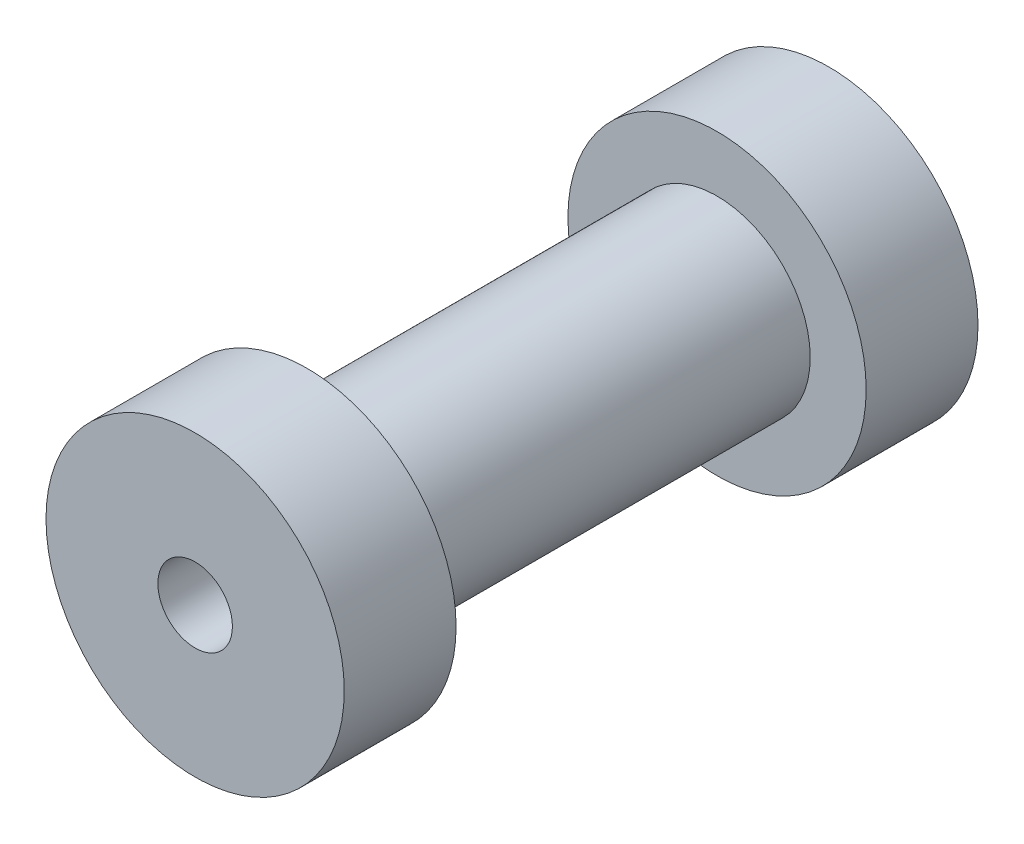
SolidWorks part; units mm, degrees
ref_plane "Alzado" through (0, 0, 0) normal (0, 0, 1) x (1, 0, 0)
ref_plane "Planta" through (0, 0, 0) normal (0, 1, 0) x (1, 0, 0)
ref_plane "Vista lateral" through (0, 0, 0) normal (1, 0, 0) x (0, 0, -1)
sketch "Croquis1" plane through (0, 0, 0) normal (0, 0, 1) x (1, 0, 0)
  circle A0 centre (0, 0) radius 4
  dimension "D1" = 8
extrude "Saliente-Extruir1" add sketch "Croquis1" along normal blind 17
sketch "Croquis2" plane through (0, 0, 17) normal (0, 0, 1) x (1, 0, 0)
  circle A0 centre (0, 0) radius 1
  dimension "D1" = 2
extrude "Cortar-Extruir1" cut sketch "Croquis2" against normal through all
ref_axis "Eje1" through (0, 0, 17) along (0, 0, -1)
sketch "Croquis3" plane through (0, 0, 0) normal (1, 0, 0) x (0, 0, -1)
  line L0 (0, 4) -> (-17, 4) construction
  line L1 (-3, 4) -> (-14, 4)
  line L2 (-3, 4) -> (-3, 2.5)
  line L3 (-3, 2.5) -> (-14, 2.5)
  line L4 (-14, 4) -> (-14, 2.5)
  line L5 (0, -4) -> (0, 4) construction
  line L6 (-17, 4) -> (-17, -4) construction
  dimension "D1" = 3
  dimension "D2" = 3
  dimension "D3" = 1.5
revolve "Cortar-Revolución1" cut sketch "Croquis3" angle 360 about axis through (0, 0, 17) along (0, 0, -1)
